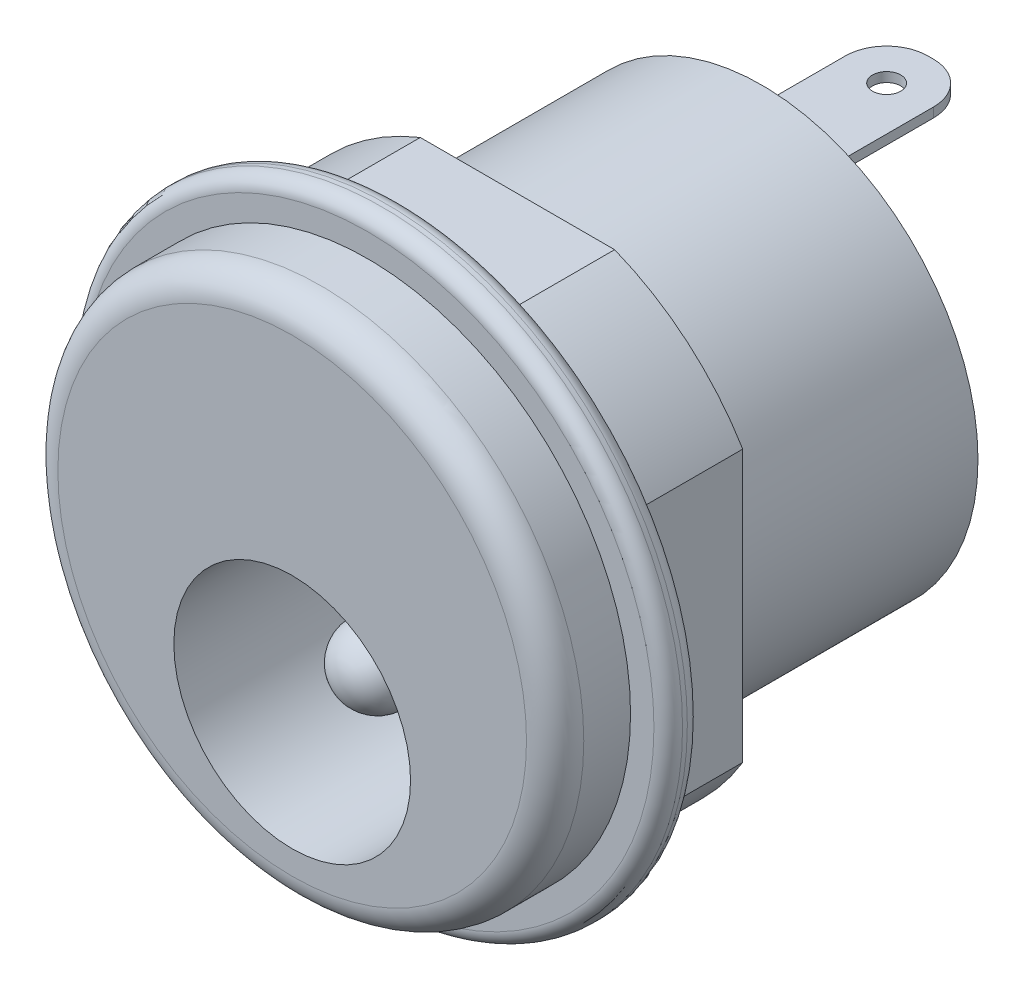
SolidWorks part; units mm, degrees
ref_plane "Front Plane" through (0, 0, 0) normal (0, 0, 1) x (1, 0, 0)
ref_plane "Top Plane" through (0, 0, 0) normal (0, 1, 0) x (1, 0, 0)
ref_plane "Right Plane" through (0, 0, 0) normal (1, 0, 0) x (0, 0, -1)
sketch "Sketch2" plane through (0, 0, 0) normal (1, 0, 0) x (0, 0, -1)
  line L0 (-7.8806, 0) -> (31.765, 0) construction
  line L1 (0, 0) -> (10.4902, 0)
  line L2 (0, 0) -> (0, 5.7531)
  line L3 (0, 5.7531) -> (10.4902, 5.7531)
  line L4 (10.4902, 0) -> (10.4902, 5.7531)
  line L6 (0, 0) -> (-2.0066, 0)
  line L7 (0, 0) -> (0, 6.9977)
  line L8 (0, 6.9977) -> (-1.2446, 6.9977)
  line L9 (-2.0066, 0) -> (-2.0066, 6.2357)
  arc A0 (-1.2446, 6.9977) -> (-2.0066, 6.2357) centre (-1.2446, 6.2357) ccw
  point P12 (-2.0066, 6.9977)
  dimension "D4" = 0.762
  dimension "D1" = 6.9977
  dimension "D2" = 2.0066
  dimension "D3" = 5.7531
  dimension "D5" = 12.4968
revolve "Revolve1" add sketch "Sketch2" angle 360 about L0
sketch "Sketch3" plane through (0, 0, 0) normal (1, 0, 0) x (0, 0, -1)
  line L0 (10.4902, 5.7531) -> (0, 5.7531) construction
  line L1 (0, 5.7531) -> (0.889, 5.7531)
  line L2 (0, 5.7531) -> (0, 7.62)
  line L3 (0.381, 8.001) -> (0.508, 8.001)
  line L4 (0.889, 5.7531) -> (0.889, 7.62)
  line L5 (0.889, 6.9977) -> (3.9878, 6.9977)
  line L6 (0.889, 6.9977) -> (0.889, 5.7531)
  line L7 (0.889, 5.7531) -> (3.9878, 5.7531)
  line L8 (3.9878, 6.9977) -> (3.9878, 5.7531)
  line L9 (-6.7703, 0) -> (15.906, 0) construction
  arc A0 (0.508, 8.001) -> (0.889, 7.62) centre (0.508, 7.62) cw
  arc A1 (0, 7.62) -> (0.381, 8.001) centre (0.381, 7.62) cw
  point P12 (0.889, 8.001)
  point P15 (0, 8.001)
  dimension "D3" = 0.381
  dimension "D1" = 0.889
  dimension "D2" = 3.9878
  dimension "D4" = 8.001
  dimension "D5" = 6.9977
revolve "Revolve2" add sketch "Sketch3" angle 360 about L9
sketch "Sketch4" plane through (0, 0, 2.0066) normal (0, 0, 1) x (1, 0, 0)
  circle A0 centre (0, -2.4511) radius 3.1496
  circle A1 centre (0, 0) radius 6.9977 construction
  point P2 (0, 6.9977)
  point P4 (0, 0.6985)
  dimension "D1" = 6.2992
extrude "Cut-Extrude1" cut sketch "Sketch4" against normal blind 8.89
sketch "Sketch5" plane through (0, 0, -6.8834) normal (0, 0, 1) x (1, 0, 0)
  circle A0 centre (0, -2.4511) radius 1
extrude "Boss-Extrude1" add sketch "Sketch5" along normal blind 7.62
fillet "Fillet1" radius 1 1 edges at (1, -2.4511, 0.7366)
sketch "Sketch6" plane through (0, 0, -10.4902) normal (0, 0, -1) x (-1, 0, 0)
  line L0 (-1.175, 4.1373) -> (1.175, 4.1373)
  line L1 (2.696, 1.175) -> (2.696, -1.175)
  point P2 (0, 4.1373)
  point P6 (2.696, 0)
extrude "Extrude-Thin1" add sketch "Sketch6" along normal blind 4.4958 thin
fillet "Fillet2" radius 1.1 4 edges at (-2.569, -1.175, -14.986) (-2.569, 1.175, -14.986) (-1.175, 4.0103, -14.986) (1.175, 4.0103, -14.986)
sketch "Sketch8" plane through (-2.442, 0, 0) normal (1, 0, 0) x (0, 0, -1)
  line L1 (14.986, 0.075) -> (14.986, -0.075) construction
  line L4 (13.886, 1.175) -> (10.4902, 1.175) construction
  point P0 (13.8118, 0)
  point P1 (14.986, 0)
  dimension "D1" = 1.175
  dimension "D2" = 1.1742
hole_wizard "Ø0.75 (0.75) Diameter Hole1" positions "Sketch12" profile "Sketch9" hole size "Ø0.75" standard "ANSI Metric" end condition through all
sketch "Sketch12" plane through (-2.442, 0, 0) normal (1, 0, 0) x (0, 0, -1)
  point P0 (13.8118, 0)
sketch "Sketch9" plane through (-2.442, 0, -13.8118) normal (0, 1, 0) x (0, 0, -1)
  line L0 (0, 0) -> (0, 5.559)
  line L1 (0, 5.559) -> (0.375, 5.559)
  line L2 (0.375, 5.559) -> (0.375, 0)
  line L5 (0.375, 0) -> (0, 0)
  line L11 (0, -6.35) -> (0, 107.95) construction
  dimension "Thru Hole Dia." = 0.75
  dimension "Thru Hole Depth" = 5.559
sketch "Sketch13" plane through (0, 4.1373, 0) normal (0, 1, 0) x (1, 0, 0)
  line L0 (0.075, 14.986) -> (-0.075, 14.986) construction
  point P0 (0, 14.986)
  point P1 (0, 13.8118)
  dimension "D1" = 1.1742
hole_wizard "Ø0.75 (0.75) Diameter Hole2" positions "Sketch15" profile "Sketch14" hole size "Ø0.75" standard "ANSI Metric" end condition through all
sketch "Sketch15" plane through (0, 4.1373, 0) normal (0, 1, 0) x (1, 0, 0)
  point P0 (0, 13.8118)
sketch "Sketch14" plane through (0, 4.1373, -13.8118) normal (1, 0, 0) x (0, 0, 1)
  line L0 (0, 0) -> (0, 12.1383)
  line L1 (0, 12.1383) -> (0.375, 12.1383)
  line L2 (0.375, 12.1383) -> (0.375, 0)
  line L5 (0.375, 0) -> (0, 0)
  line L11 (0, -6.35) -> (0, 107.95) construction
  dimension "Thru Hole Dia." = 0.75
  dimension "Thru Hole Depth" = 12.1383
sketch "Sketch16" plane through (0, 0, -10.4902) normal (0, 0, -1) x (-1, 0, 0)
  line L1 (-5.9944, 6.5024) -> (5.9944, 6.5024)
  line L2 (-5.9944, 6.5024) -> (-5.9944, -6.5024)
  line L3 (-5.9944, -6.5024) -> (5.9944, -6.5024)
  line L4 (5.9944, 6.5024) -> (5.9944, -6.5024)
  point P4 (-5.9944, 0)
  point P5 (0, 6.5024)
  dimension "D1" = 11.9888
  dimension "D2" = 13.0048
extrude "Cut-Extrude2" cut sketch "Sketch16" against normal up to surface (9.6012 mm away) flip side to cut up to face at (7.62, 0, -0.889)
